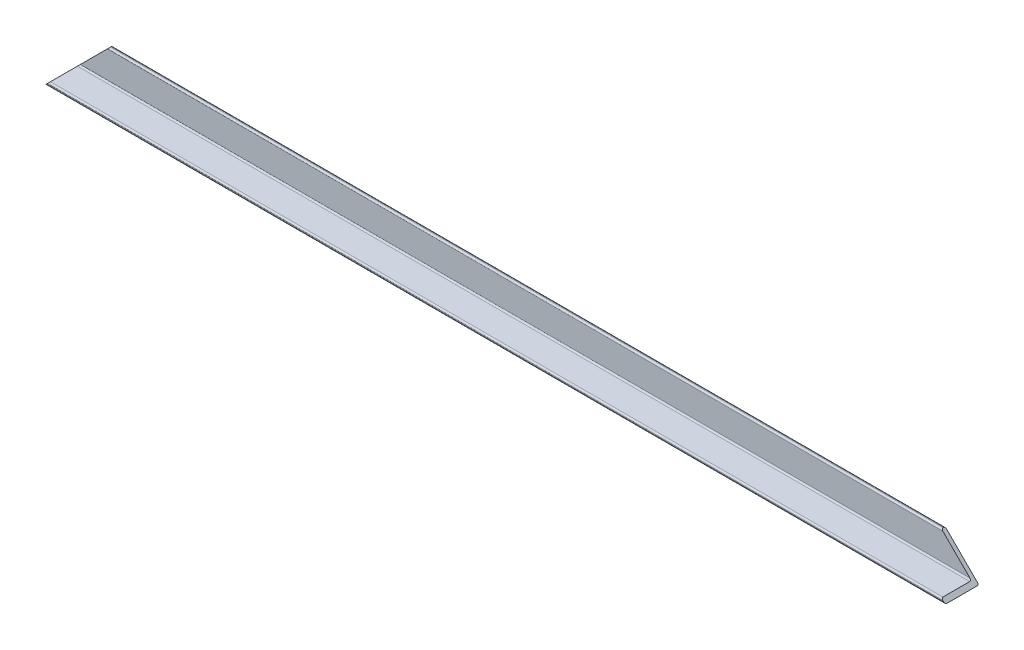
SolidWorks part; units mm, degrees
ref_plane "Front Plane" through (0, 0, 0) normal (0, 0, 1) x (1, 0, 0)
ref_plane "Top Plane" through (0, 0, 0) normal (0, 1, 0) x (1, 0, 0)
ref_plane "Right Plane" through (0, 0, 0) normal (1, 0, 0) x (0, 0, -1)
sketch "Sketch1" plane through (0, 0, 0) normal (0, 1, 0) x (1, 0, 0)
  line L1 (-307.5, 11.25) -> (307.5, 11.25)
  line L2 (-307.5, 11.25) -> (-307.5, -11.25)
  line L3 (-307.5, -11.25) -> (307.5, -11.25)
  line L4 (307.5, 11.25) -> (307.5, -11.25)
  line L5 (-307.5, 11.25) -> (307.5, -11.25) construction
  line L6 (-307.5, -11.25) -> (307.5, 11.25) construction
  point P0 (0, 0)
  dimension "D1" = 615
  dimension "D2" = 22.5
extrude "Boss-Extrude1" add sketch "Sketch1" along normal blind 2.5
sketch "Sketch2" plane through (0, 2.5, 0) normal (0, 1, 0) x (1, 0, 0)
  line L0 (307.5, -11.25) -> (307.5, 11.25) construction
  line L1 (-307.5, 11.25) -> (307.5, 11.25)
  line L2 (-307.5, 11.25) -> (-307.5, 8.75)
  line L3 (-307.5, 8.75) -> (307.5, 8.75)
  line L4 (307.5, 11.25) -> (307.5, 8.75)
  dimension "D1" = 2.5
extrude "Boss-Extrude2" add sketch "Sketch2" along normal blind 20
sketch "Sketch3" plane through (0, 0, -8.75) normal (0, 0, 1) x (1, 0, 0)
  line L0 (-307.5, 22.5) -> (-307.5, -7.5)
  line L1 (-307.5, 22.5) -> (307.5, 22.5) construction
  line L2 (-307.5, -7.5) -> (-277.5, 22.5)
  line L3 (-277.5, 22.5) -> (-307.5, 22.5)
  line L4 (307.5, 22.5) -> (307.5, -7.5)
  line L5 (307.5, -7.5) -> (277.5, 22.5)
  line L6 (277.5, 22.5) -> (307.5, 22.5)
  dimension "D1" = 45
  dimension "D2" = 30
  dimension "D3" = 30
  dimension "D4" = 45
extrude "Cut-Extrude1" cut sketch "Sketch3" against normal blind 25 and the other way through all
fillet "Fillet2" radius 1 6 edges at (0, 0, -11.25) (0, 0, 11.25) (0, 2.5, 11.25) (0, 22.5, -11.25) (0, 22.5, -8.75) (0, 2.5, -8.75)
